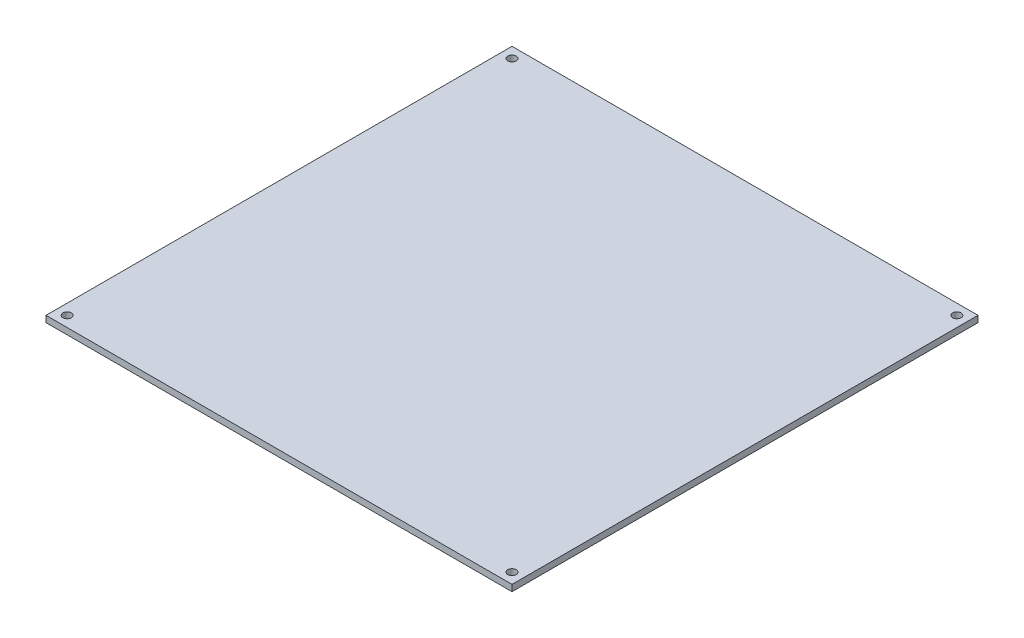
SolidWorks part; units mm, degrees
ref_plane "Front" through (0, 0, 0) normal (0, 0, 1) x (1, 0, 0)
ref_plane "Top" through (0, 0, 0) normal (0, 1, 0) x (1, 0, 0)
ref_plane "Right" through (0, 0, 0) normal (1, 0, 0) x (0, 0, -1)
sketch "Sketch1" plane through (0, 0, 0) normal (0, 1, 0) x (1, 0, 0)
  line L1 (-110, 110) -> (110, 110)
  line L2 (-110, 110) -> (-110, -110)
  line L3 (-110, -110) -> (110, -110)
  line L4 (110, 110) -> (110, -110)
  line L5 (-110, 110) -> (110, -110) construction
  line L6 (-110, -110) -> (110, 110) construction
  circle A1 centre (105, 105) radius 2
  circle A2 centre (105, -105) radius 2
  circle A3 centre (-105, -105) radius 2
  circle A4 centre (-105, 105) radius 2
  point P0 (0, 0)
  point P17 (0, 0)
  dimension "D4" = 5
  dimension "D3" = 4
  dimension "D1" = 220
  dimension "D2" = 220
  dimension "D5" = 4
extrude "Boss-Extrude1" add sketch "Sketch1" along normal blind 3
